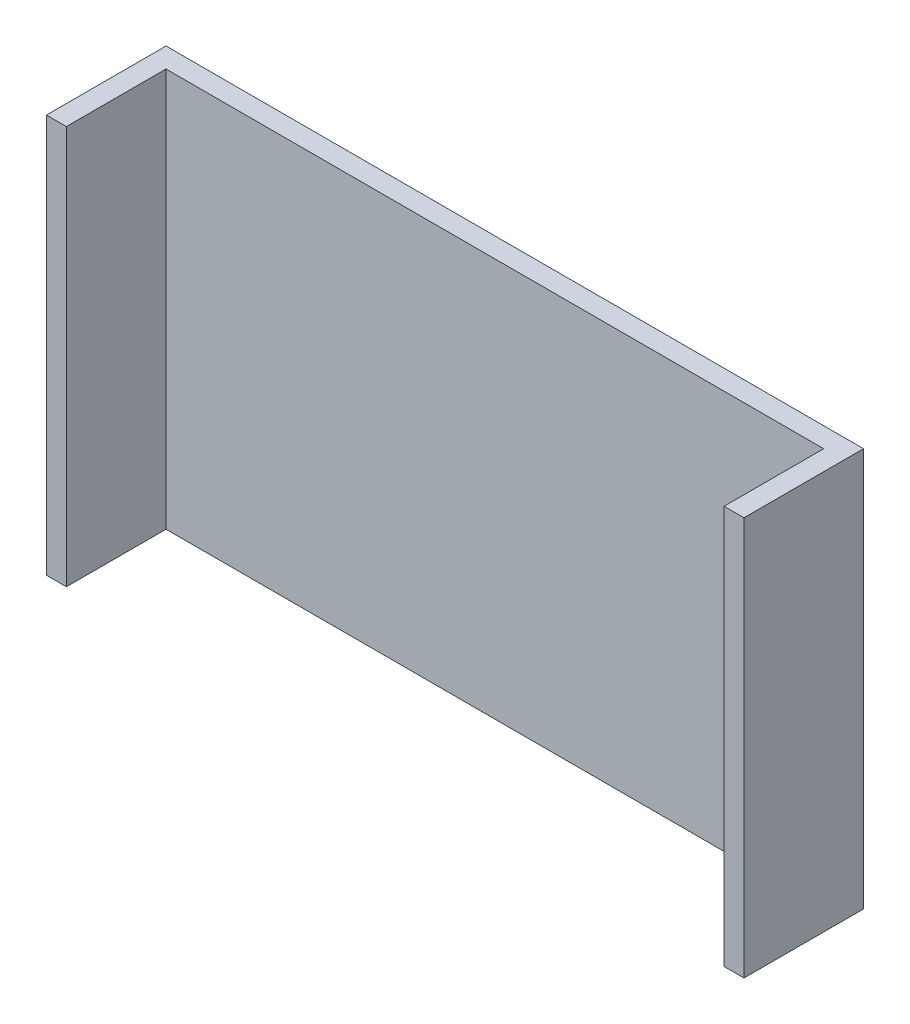
SolidWorks part; units mm, degrees
ref_plane "Front Plane" through (0, 0, 0) normal (0, 0, 1) x (1, 0, 0)
ref_plane "Top Plane" through (0, 0, 0) normal (0, 1, 0) x (1, 0, 0)
ref_plane "Right Plane" through (0, 0, 0) normal (1, 0, 0) x (0, 0, -1)
sketch "Sketch1" plane through (0, 0, 0) normal (0, 0, 1) x (1, 0, 0)
  line L0 (-33, 20) -> (-33, -20)
  line L1 (-35, 20) -> (35, 20)
  line L2 (-35, 20) -> (-35, -20)
  line L3 (-35, -20) -> (35, -20)
  line L4 (35, 20) -> (35, -20)
  line L5 (0, -20) -> (0, 20) construction
  line L6 (-35, 0) -> (35, 0) construction
  line L7 (33, 20) -> (33, -20)
  point P0 (0, 0)
  dimension "D1" = 40
  dimension "D2" = 70
  dimension "D3" = 2
  dimension "D4" = 2
extrude "Boss-Extrude1" add sketch "Sketch1" along normal blind 2 contours L3 L4 L1 L2
sketch "Sketch2" plane through (0, 0, 2) normal (0, 0, 1) x (1, 0, 0)
  line L0 (-33, 20) -> (-33, -20)
  line L1 (-35, 20) -> (35, 20)
  line L2 (-35, 20) -> (-35, -20)
  line L3 (-35, -20) -> (35, -20)
  line L4 (35, 20) -> (35, -20)
  line L5 (0, -20) -> (0, 20) construction
  line L6 (-35, 0) -> (35, 0) construction
  line L7 (33, 20) -> (33, -20)
  point P0 (0, 0)
  line M9 (-35, 20) -> (-35, -20)
  line M10 (-35, -20) -> (35, -20)
  line M11 (35, -20) -> (35, 20)
  line M12 (35, 20) -> (-35, 20)
extrude "Boss-Extrude2" add sketch "Sketch2" along normal blind 10 contours L0 M12 M9 M10 | L7 L3 M12 M11
